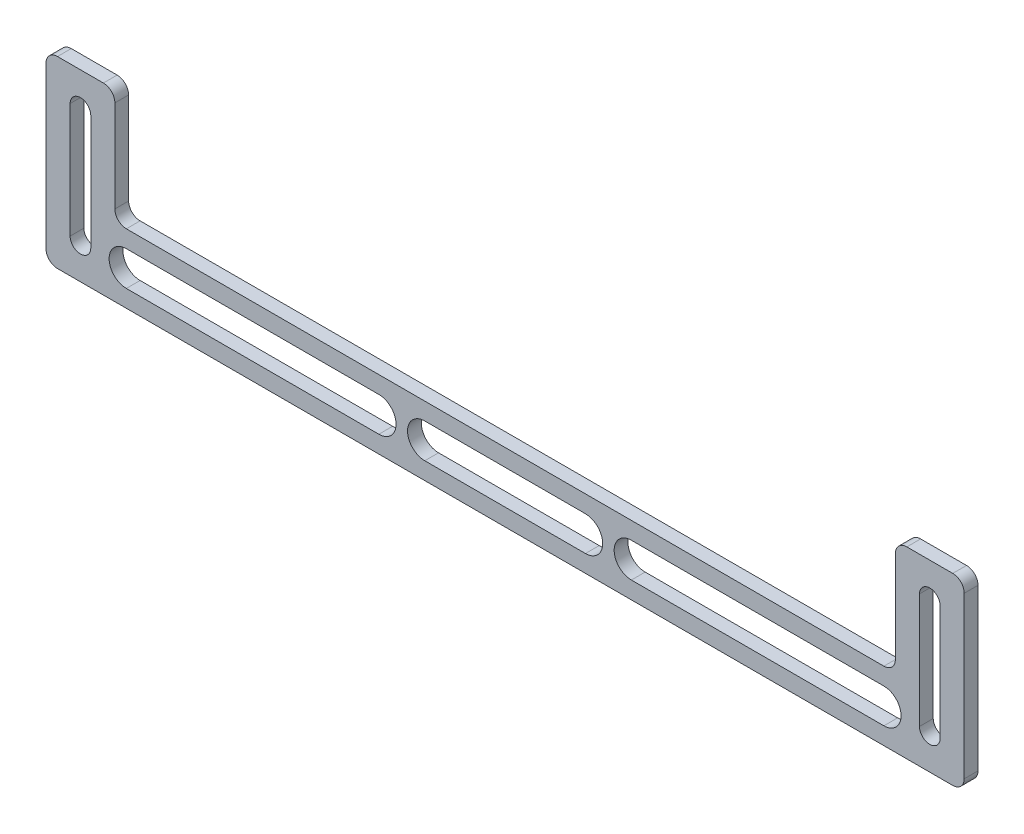
SolidWorks part; units mm, degrees
material "Q235"
ref_plane "前视基准面" through (0, 0, 0) normal (0, 0, 1) x (1, 0, 0)
ref_plane "上视基准面" through (0, 0, 0) normal (0, 1, 0) x (1, 0, 0)
ref_plane "右视基准面" through (0, 0, 0) normal (1, 0, 0) x (0, 0, -1)
sketch "草图1" plane through (0, 0, 0) normal (0, 0, 1) x (1, 0, 0)
  line L0 (0, 0) -> (0, 86.0207) construction
  line L1 (-221.7896, 0) -> (221.7896, 0) construction
  line L2 (0, 0) -> (0, -90.7019) construction
  line L3 (-170, 15) -> (170, 15)
  line L4 (170, 15) -> (170, 65)
  line L5 (170, 65) -> (200, 65)
  line L6 (200, 65) -> (200, -15)
  line L7 (200, -15) -> (-200, -15)
  line L8 (-35, 0) -> (35, 0) construction
  line L9 (-35, 7.5) -> (35, 7.5)
  line L10 (-35, -7.5) -> (35, -7.5)
  line L11 (55, 0) -> (165, 0) construction
  line L12 (55, 7.5) -> (165, 7.5)
  line L13 (55, -7.5) -> (165, -7.5)
  line L14 (185, 50) -> (185, 0) construction
  line L15 (189.5, 50) -> (189.5, 0)
  line L16 (180.5, 50) -> (180.5, 0)
  line L17 (-200, 65) -> (-200, -15)
  line L18 (-170, 65) -> (-200, 65)
  line L19 (-170, 15) -> (-170, 65)
  line L20 (-185, 50) -> (-185, 0) construction
  line L21 (-189.5, 50) -> (-189.5, 0)
  line L22 (-180.5, 50) -> (-180.5, 0)
  line L23 (-55, 0) -> (-165, 0) construction
  line L24 (-55, 7.5) -> (-165, 7.5)
  line L25 (-55, -7.5) -> (-165, -7.5)
  arc A0 (-35, 7.5) -> (-35, -7.5) centre (-35, 0) ccw
  arc A1 (35, -7.5) -> (35, 7.5) centre (35, 0) ccw
  arc A2 (55, 7.5) -> (55, -7.5) centre (55, 0) ccw
  arc A3 (165, -7.5) -> (165, 7.5) centre (165, 0) ccw
  arc A4 (189.5, 50) -> (180.5, 50) centre (185, 50) ccw
  arc A5 (180.5, 0) -> (189.5, 0) centre (185, 0) ccw
  arc A6 (-189.5, 50) -> (-180.5, 50) centre (-185, 50) cw
  arc A7 (-180.5, 0) -> (-189.5, 0) centre (-185, 0) cw
  arc A8 (-55, 7.5) -> (-55, -7.5) centre (-55, 0) cw
  arc A9 (-165, -7.5) -> (-165, 7.5) centre (-165, 0) cw
  point P13 (0, 0)
  point P20 (110, 0)
  point P27 (185, 25)
  point P35 (0, -15)
  point P38 (0, 15)
  point P40 (-185, 25)
  point P47 (-110, 0)
  dimension "D7" = 7.5
  dimension "D8" = 7.5
  dimension "D13" = 4.5
  dimension "D1" = 30
  dimension "D2" = 400
  dimension "D3" = 30
  dimension "D4" = 15
  dimension "D5" = 80
  dimension "D6" = 185
  dimension "D9" = 70
  dimension "D10" = 110
  dimension "D11" = 110
  dimension "D12" = 50
extrude "凸台-拉伸1" add sketch "草图1" along normal blind 6
fillet "圆角1" radius 5 8 edges at (-170, 65, 3) (-200, 65, 3) (-200, -15, 3) (200, -15, 3) (170, 65, 3) (200, 65, 3) (170, 15, 3) (-170, 15, 3)
